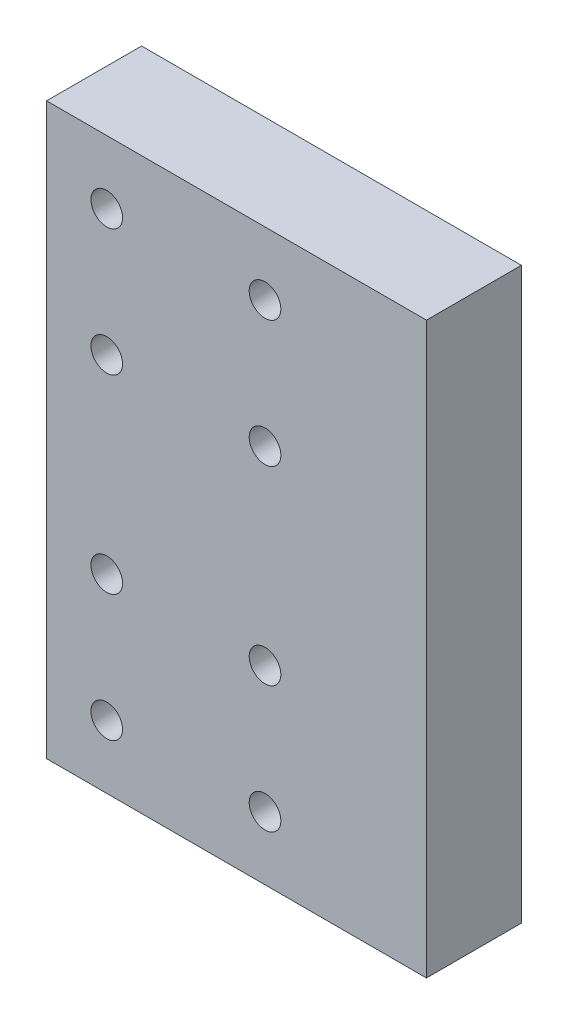
SolidWorks part; units mm, degrees
ref_plane "Front" through (0, 0, 0) normal (0, 0, 1) x (1, 0, 0)
ref_plane "Top" through (0, 0, 0) normal (0, 1, 0) x (1, 0, 0)
ref_plane "Right" through (0, 0, 0) normal (1, 0, 0) x (0, 0, -1)
sketch "Esquisse1" plane through (0, 0, 0) normal (0, 0, 1) x (1, 0, 0)
  line L1 (0, 0) -> (60, 0)
  line L2 (0, 0) -> (0, 90)
  line L3 (0, 90) -> (60, 90)
  line L4 (60, 0) -> (60, 90)
  dimension "D1" = 60
  dimension "D2" = 90
extrude "Boss.-Extru.1" add sketch "Esquisse1" along normal blind 15
sketch "Esquisse2" plane through (0, 0, 15) normal (0, 0, 1) x (1, 0, 0)
  line L0 (22, 0) -> (22, 90) construction
  line L1 (0, 0) -> (60, 0) construction
  line L2 (60, 90) -> (0, 90) construction
  line L3 (22, 45) -> (0, 45) construction
  line L4 (0, 90) -> (0, 0) construction
  line L5 (22, 20) -> (6.6007, 20) construction
  line L6 (22, 70) -> (6.6007, 70) construction
  circle A0 centre (9.5, 10) radius 2.5
  circle A1 centre (34.5, 10) radius 2.5
  circle A2 centre (34.5, 30) radius 2.5
  circle A3 centre (9.5, 30) radius 2.5
  circle A4 centre (9.5, 60) radius 2.5
  circle A5 centre (34.5, 60) radius 2.5
  circle A6 centre (34.5, 80) radius 2.5
  circle A7 centre (9.5, 80) radius 2.5
  dimension "D1" = 25
  dimension "D2" = 20
  dimension "D4" = 5
  dimension "D3" = 25
  dimension "D5" = 22
extrude "Enlèv. mat.-Extru.1" cut sketch "Esquisse2" against normal through all both and the other way through all
